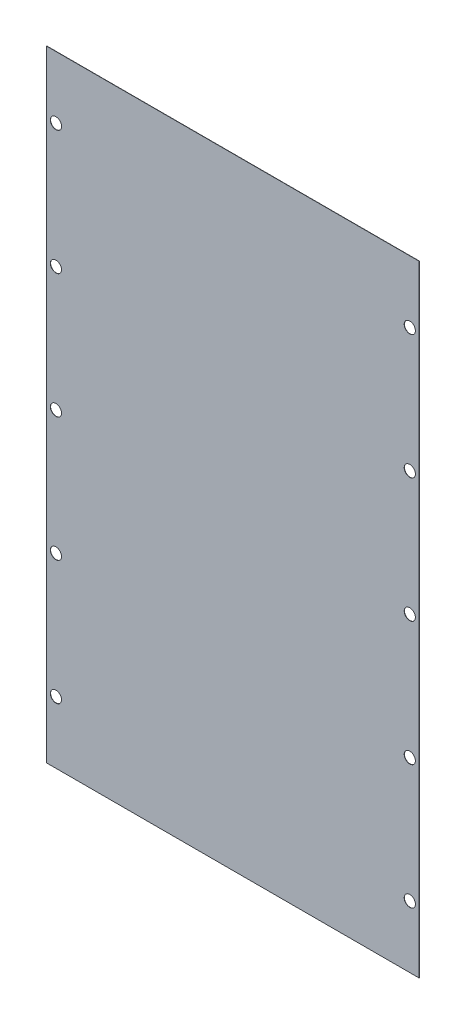
SolidWorks part; units mm, degrees
ref_plane "Front Plane" through (0, 0, 0) normal (0, 0, 1) x (1, 0, 0)
ref_plane "Top Plane" through (0, 0, 0) normal (0, 1, 0) x (1, 0, 0)
ref_plane "Right Plane" through (0, 0, 0) normal (1, 0, 0) x (0, 0, -1)
ref_plane "Plane1" through (0, 0, -0.1) normal (0, 0, -1) x (-1, 0, 0)
sketch "Sketch1" plane through (0, 0, -0.1) normal (0, 0, -1) x (-1, 0, 0)
  line L0 (-325, 500) -> (-625, 500)
  line L1 (-625, 500) -> (-625, 0)
  line L2 (-625, 0) -> (-325, 0)
  line L3 (-325, 0) -> (-325, 500)
  dimension "D1" = 500
  dimension "D2" = 300
extrude "Boss-Extrude1" add sketch "Sketch1" against normal blind 0.2
sketch "Sketch2" plane through (0, 0, -0.1) normal (0, 0, -1) x (-1, 0, 0)
  line L0 (-332.5, 498.0784) -> (-332.5, 485.6108) construction
  line L1 (-332.5, 0) -> (-332.5, 500) construction
  line L3 (-325, 500) -> (-625, 500) construction
  line L4 (-475, 500) -> (-475, 0) construction
  line L5 (-625, 0) -> (-325, 0) construction
  circle A0 centre (-332.5, 450) radius 4.5
  circle A1 centre (-332.5, 350) radius 4.5
  circle A2 centre (-332.5, 250) radius 4.5
  circle A3 centre (-332.5, 150) radius 4.5
  circle A4 centre (-332.5, 50) radius 4.5
  circle A5 centre (-617.5, 450) radius 4.5
  circle A6 centre (-617.5, 350) radius 4.5
  circle A7 centre (-617.5, 250) radius 4.5
  circle A8 centre (-617.5, 150) radius 4.5
  circle A9 centre (-617.5, 50) radius 4.5
  dimension "D1" = 9
  dimension "D2" = 50
  dimension "D3" = 5
extrude "M8 clearance - 9mm - thru" cut sketch "Sketch2" against normal through all
